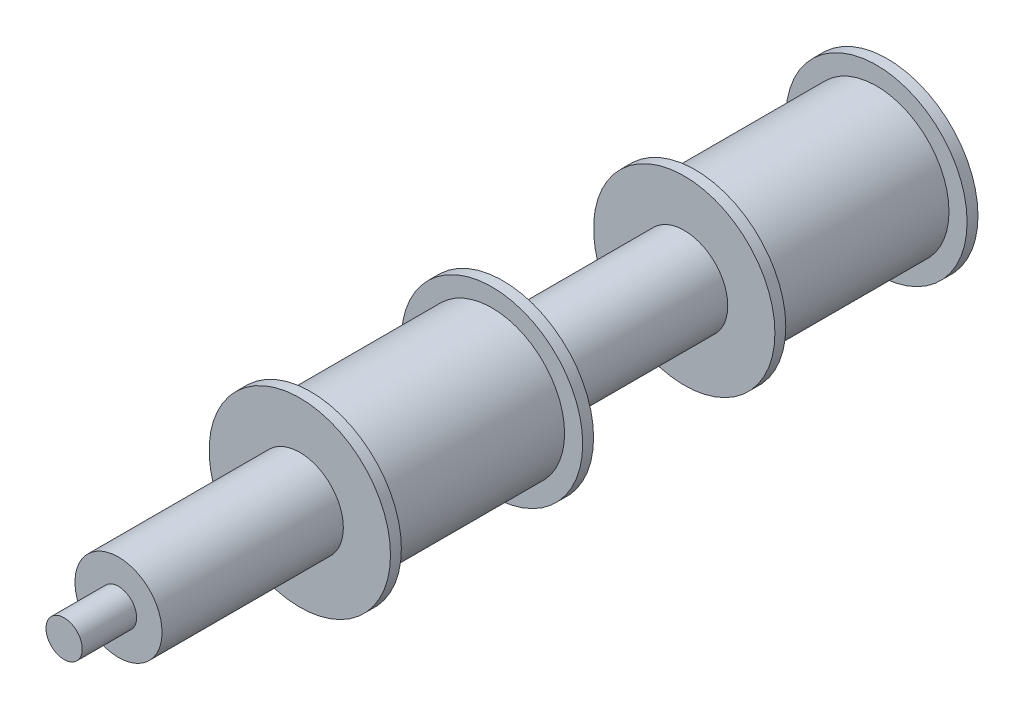
SolidWorks part; units mm, degrees
ref_plane "前视基准面" through (0, 0, 0) normal (0, 0, 1) x (1, 0, 0)
ref_plane "上视基准面" through (0, 0, 0) normal (0, 1, 0) x (1, 0, 0)
ref_plane "右视基准面" through (0, 0, 0) normal (1, 0, 0) x (0, 0, -1)
sketch "草图1" plane through (0, 0, 0) normal (0, 0, 1) x (1, 0, 0)
  circle A0 centre (0, 0) radius 25
extrude "凸台-拉伸1" add sketch "草图1" along normal blind 3
sketch "草图2" plane through (0, 0, 3) normal (0, 0, 1) x (1, 0, 0)
  circle A0 centre (0, 0) radius 20
extrude "凸台-拉伸2" add sketch "草图2" along normal blind 50
sketch "草图3" plane through (0, 0, 53) normal (0, 0, 1) x (1, 0, 0)
  circle A0 centre (0, 0) radius 25 construction
  circle A1 centre (0, 0) radius 25
extrude "凸台-拉伸3" add sketch "草图3" along normal blind 3
sketch "草图4" plane through (0, 0, 56) normal (0, 0, 1) x (1, 0, 0)
  circle A0 centre (0, 0) radius 12
extrude "凸台-拉伸4" add sketch "草图4" along normal blind 50
sketch "草图5" plane through (0, 0, 106) normal (0, 0, 1) x (1, 0, 0)
  circle A0 centre (0, 0) radius 25 construction
  circle A1 centre (0, 0) radius 25
extrude "凸台-拉伸5" add sketch "草图5" along normal blind 3
sketch "草图6" plane through (0, 0, 109) normal (0, 0, 1) x (1, 0, 0)
  circle A0 centre (0, 0) radius 20 construction
  circle A1 centre (0, 0) radius 20
extrude "凸台-拉伸6" add sketch "草图6" along normal blind 50
sketch "草图8" plane through (0, 0, 159) normal (0, 0, 1) x (1, 0, 0)
  circle A0 centre (0, 0) radius 25 construction
  circle A1 centre (0, 0) radius 25
extrude "凸台-拉伸7" add sketch "草图8" along normal blind 3
sketch "草图9" plane through (0, 0, 162) normal (0, 0, 1) x (1, 0, 0)
  circle A0 centre (0, 0) radius 12 construction
  circle A3 centre (0, 0) radius 12
extrude "凸台-拉伸8" add sketch "草图9" along normal blind 50
sketch "草图10" plane through (0, 0, 212) normal (0, 0, 1) x (1, 0, 0)
  circle A0 centre (0, 0) radius 5
extrude "凸台-拉伸9" add sketch "草图10" along normal blind 15
